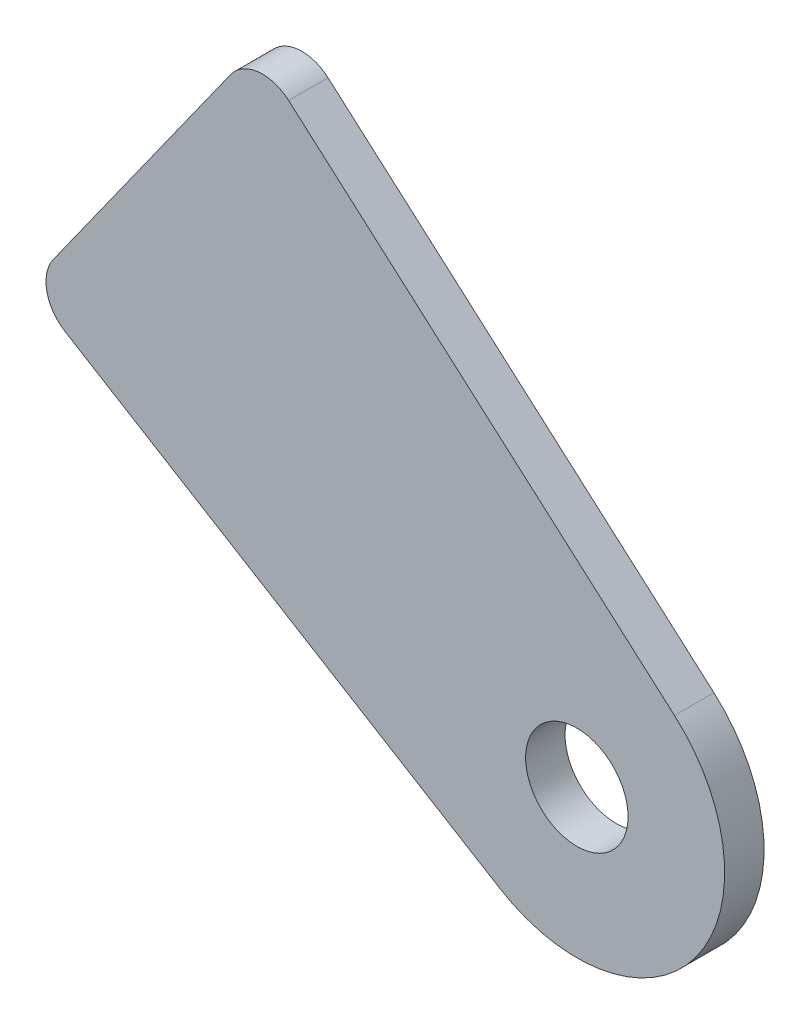
SolidWorks part; units mm, degrees
material "ASTM A36 Steel"
ref_plane "Front Plane" through (0, 0, 0) normal (0, 0, 1) x (1, 0, 0)
ref_plane "Top Plane" through (0, 0, 0) normal (0, 1, 0) x (1, 0, 0)
ref_plane "Right Plane" through (0, 0, 0) normal (1, 0, 0) x (0, 0, -1)
sketch "Sketch1" plane through (0, 0, 0) normal (0, 0, 1) x (1, 0, 0)
  line L0 (24.3078, -29.6632) -> (-6.0555, -11.1634)
  line L1 (35.5567, -14.379) -> (8.5778, 9.3654)
  line L2 (-6.0555, -11.1634) -> (8.5778, 9.3654)
  circle A2 centre (29.2638, -21.5291) radius 3.3
  circle A4 centre (29.2638, -21.5291) radius 9.525 construction
  arc A6 (35.5567, -14.379) -> (24.3078, -29.6632) centre (29.2638, -21.5291) cw
  point P2 (0, 0)
  point P5 (0, 0)
  dimension "D4" = 19.05
  dimension "D5" = 6.6
extrude "Boss-Extrude3" add sketch "Sketch1" along normal blind 2.54
fillet "Fillet1" radius 2.54 1 edges at (-6.0555, -11.1634, 1.27)
fillet "Fillet2" radius 2.54 1 edges at (8.5778, 9.3654, 1.27)
